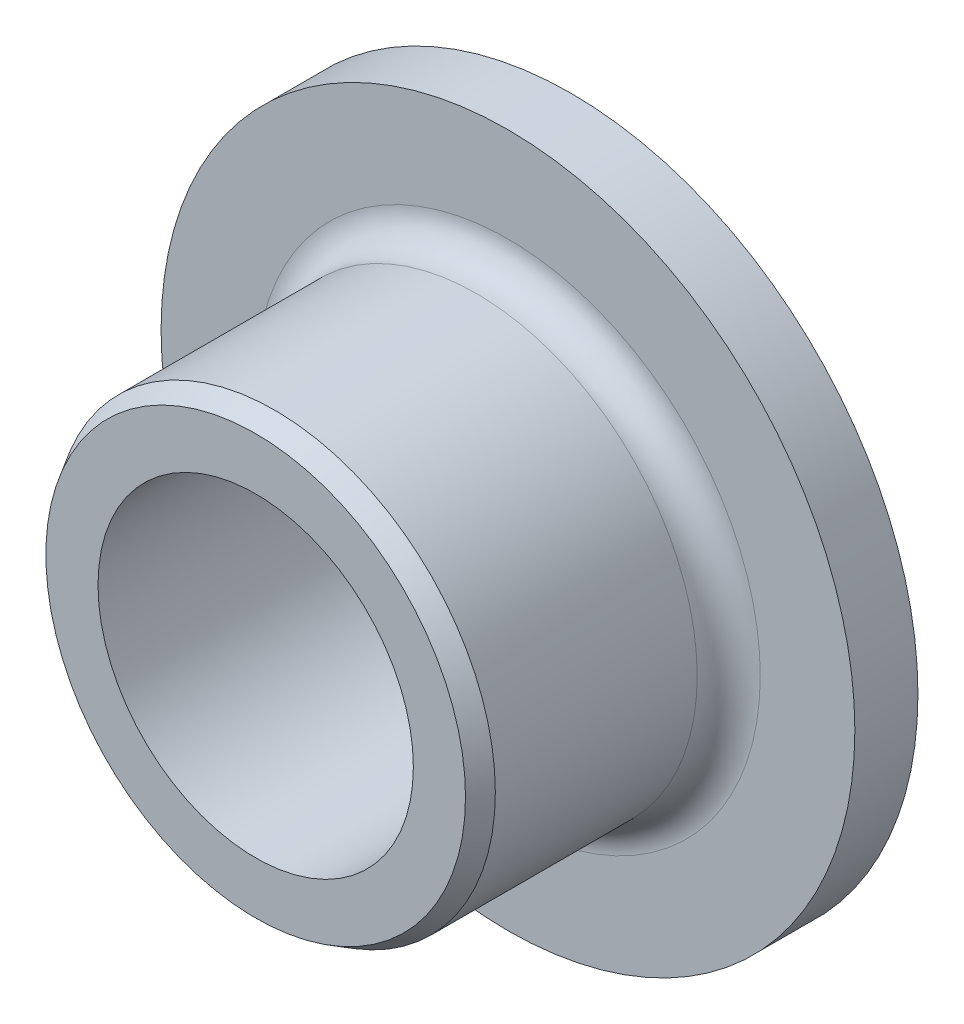
SolidWorks part; units mm, degrees
ref_plane "Front Plane" through (0, 0, 0) normal (0, 0, 1) x (1, 0, 0)
ref_plane "Top Plane" through (0, 0, 0) normal (0, 1, 0) x (1, 0, 0)
ref_plane "Right Plane" through (0, 0, 0) normal (1, 0, 0) x (0, 0, -1)
sketch "Sketch1" plane through (0, 0, 0) normal (0, 1, 0) x (1, 0, 0)
  line L0 (3.5, -4.7) -> (3.5, -1.5)
  line L1 (4, -1) -> (5.5, -1)
  line L2 (5.5, -1) -> (5.5, 0)
  line L3 (5.5, 0) -> (2.5, 0)
  line L4 (2.5, 0) -> (2.5, -5)
  line L5 (2.5, -5) -> (3.3268, -5)
  line L6 (3.3268, -5) -> (3.5, -4.7)
  line L7 (0, 0) -> (0, -5) construction
  arc A0 (3.5, -1.5) -> (4, -1) centre (4, -1.5) cw
  dimension "D1" = 0.5
  dimension "D2" = 5
  dimension "D3" = 6.6536
  dimension "D4" = 7
  dimension "D5" = 11
  dimension "D6" = 1
  dimension "D7" = 4.7
  dimension "D8" = 5
revolve "Revolve1" add sketch "Sketch1" angle 360 about L7
